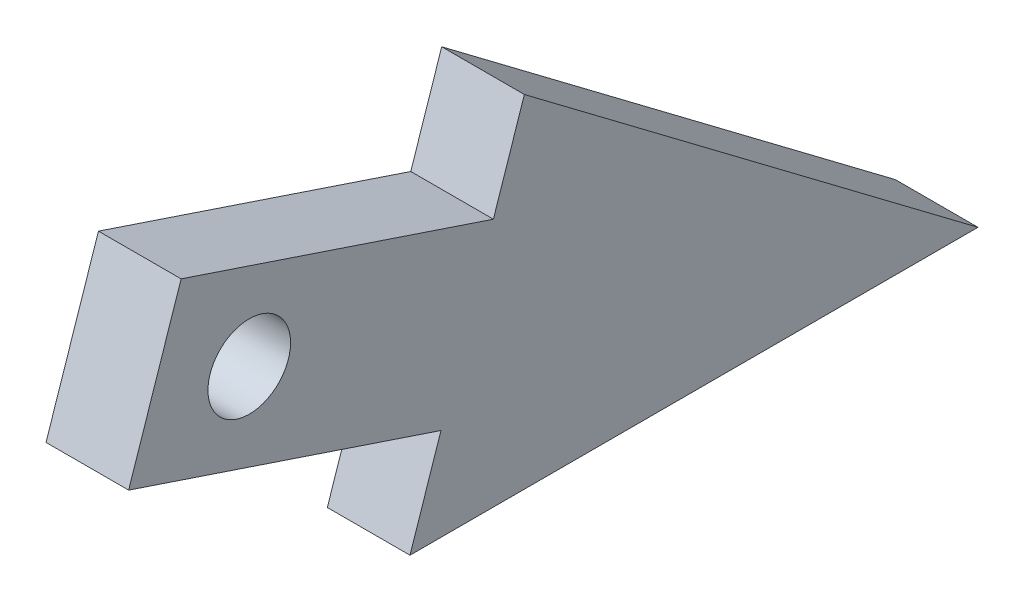
SolidWorks part; units mm, degrees
material "TIMETAL 35A CP Titanium (ASTM Grade 1) 99.1 Ti"
ref_plane "Front Plane" through (0, 0, 0) normal (0, 0, 1) x (1, 0, 0)
ref_plane "Top Plane" through (0, 0, 0) normal (0, 1, 0) x (1, 0, 0)
ref_plane "Right Plane" through (0, 0, 0) normal (1, 0, 0) x (0, 0, -1)
sketch "Sketch2" plane through (0, 0, 0) normal (1, 0, 0) x (0, 0, -1)
  line L0 (0, 0) -> (0, 74.93) construction
  line L1 (223.9422, 0) -> (49.3911, 0)
  line L2 (223.9422, 0) -> (0, 74.93) construction
  line L3 (-37.0618, 60.5466) -> (58.9058, 28.4363)
  line L4 (49.3911, 0) -> (58.9058, 28.4363)
  line L5 (-37.0618, 60.5466) -> (-20.9427, 108.7214)
  line L6 (223.9422, 0) -> (84.5395, 105.0474)
  line L7 (84.5395, 105.0474) -> (75.0248, 76.6111)
  line L8 (-20.9427, 108.7214) -> (75.0248, 76.6111)
  circle A0 centre (0, 74.93) radius 12.7
  dimension "D2" = 25.4
  dimension "D1" = 74.93
  dimension "D3" = 18.5
  dimension "D4" = 71.5
  dimension "D5" = 25.4
  dimension "D6" = 90
extrude "Boss-Extrude1" add sketch "Sketch2" along normal blind 25.4
